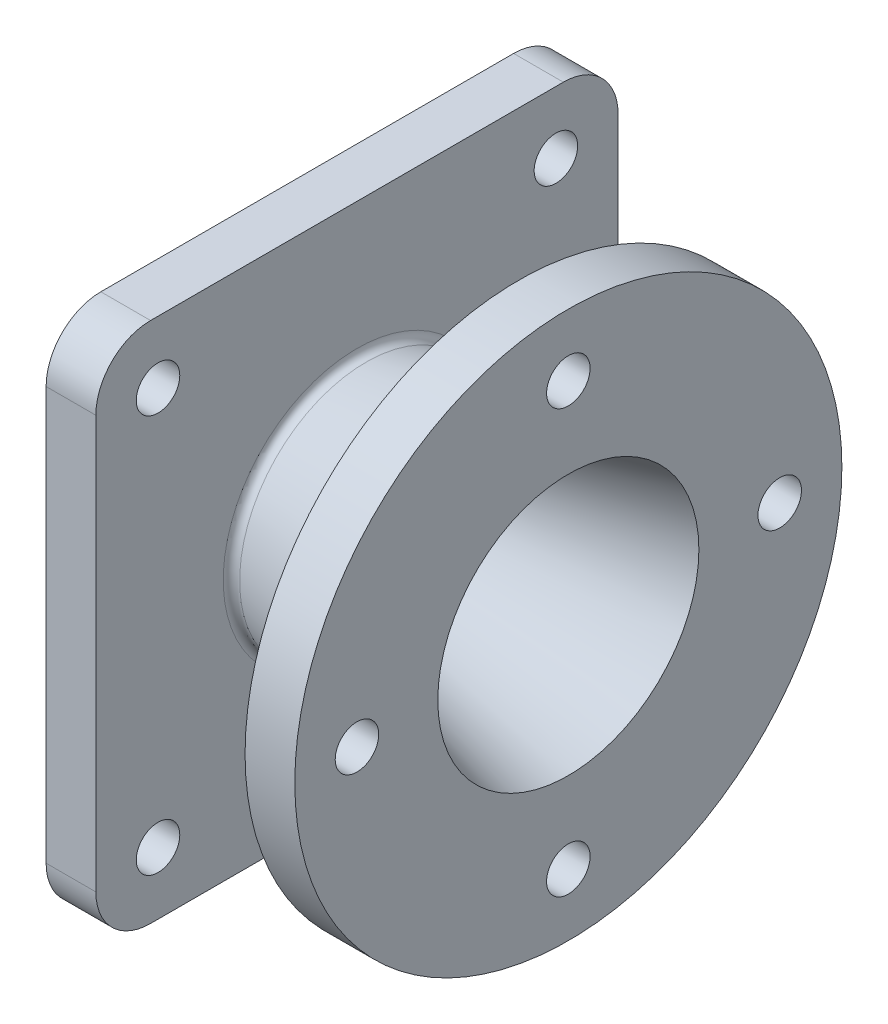
SolidWorks part; units mm, degrees
material "Сталь 12Х17 ГОСТ 5632-72"
ref_plane "Спереди" through (0, 0, 0) normal (0, 0, 1) x (1, 0, 0)
ref_plane "Сверху" through (0, 0, 0) normal (0, 1, 0) x (1, 0, 0)
ref_plane "Справа" through (0, 0, 0) normal (1, 0, 0) x (0, 0, -1)
sketch "Эскиз1" plane through (0, 0, 0) normal (0, 0, 1) x (1, 0, 0)
  line L0 (0, 0) -> (-243.1706, 0) construction
  line L1 (0, 52.5) -> (0, 110)
  line L2 (0, 110) -> (-20, 110)
  line L3 (-20, 110) -> (-20, 65)
  line L4 (-85, 50) -> (-20, 65)
  line L5 (-105, 35) -> (-113, 35)
  line L6 (-85, 50) -> (-85, 105)
  line L7 (-85, 105) -> (-105, 105)
  line L8 (-105, 105) -> (-105, 62.5)
  line L9 (-105, 62.5) -> (-130, 62.5)
  line L10 (-130, 62.5) -> (-130, 28.7125)
  line L11 (-113, 35) -> (-113, 28.7125)
  line L12 (0, 52.5) -> (-105, 25)
  line L13 (-105, 25) -> (-105, 35)
  line L14 (-113, 28.7125) -> (-130, 28.7125)
  dimension "D1" = 220
  dimension "D2" = 20
  dimension "D3" = 105
  dimension "D4" = 100
  dimension "D5" = 130
  dimension "D6" = 65
  dimension "D7" = 25
  dimension "D8" = 210
  dimension "D9" = 105
  dimension "D10" = 125
  dimension "D11" = 70
  dimension "D12" = 50
  dimension "D13" = 57.425
  dimension "D14" = 8
revolve "Повернуть1" add sketch "Эскиз1" angle 360 about L0
cosmetic thread "Условное изображение резьбы1" parameters "D2"=64
sketch "Эскиз2" plane through (0, 0, 0) normal (1, 0, 0) x (0, 0, -1)
  circle A0 centre (0, 85) radius 8.75
  dimension "D2" = 17.5
  dimension "D1" = 85
extrude "Вырез-Вытянуть1" cut sketch "Эскиз2" against normal up to next
pattern_circular "Круговой массив1" count 4 over 360 about axis through (0, 0, 0) along (1, 0, 0) of "Вырез-Вытянуть1"
sketch "Эскиз3" plane through (-105, 0, 0) normal (-1, 0, 0) x (0, 0, 1)
  line L1 (-105, -105) -> (105, -105)
  line L2 (-105, -105) -> (-105, 105)
  line L3 (-105, 105) -> (105, 105)
  line L4 (105, -105) -> (105, 105)
  line L5 (-105, -105) -> (105, 105) construction
  line L6 (-105, 105) -> (105, -105) construction
  circle A4 centre (0, 0) radius 105 construction
  circle A5 centre (0, 0) radius 35 construction
  circle A6 centre (0, 0) radius 35
  point P0 (0, 0)
extrude "Бобышка-Вытянуть1" add sketch "Эскиз3" against normal up to surface (20 mm away) up to face at (-85, 0, -105)
sketch "Эскиз4" plane through (-105, 0, 0) normal (-1, 0, 0) x (0, 0, 1)
  line L0 (0, 0) -> (105, 105) construction
  circle A0 centre (80, 80) radius 8.75
  dimension "D1" = 80
  dimension "D2" = 17.5
extrude "Вырез-Вытянуть2" cut sketch "Эскиз4" against normal up to surface (20 mm away) up to face at (-85, 0, 0)
fillet "Скругление1" radius 22 4 edges at (-95, 105, -105) (-95, -105, -105) (-95, -105, 105) (-95, 105, 105)
pattern_circular "Круговой массив5" count 4 over 360 about axis through (0, 0, 0) along (1, 0, 0) of "Вырез-Вытянуть2"
chamfer "Фаска1" distance 3.2875 angle 45 1 edges at (-130, 0, -28.7125)
fillet "Скругление2" radius 3 2 edges at (-20, 0, -65) (-85, 0, -50)
